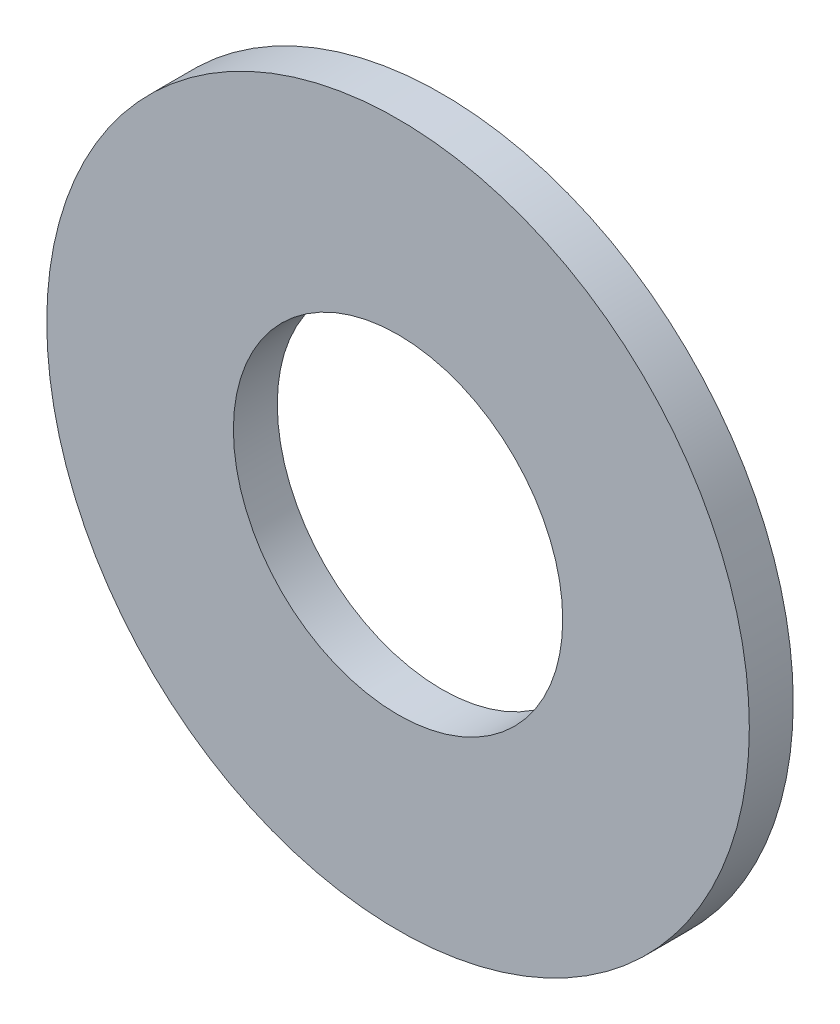
SolidWorks part; units mm, degrees
ref_plane "Front Plane" through (0, 0, 0) normal (0, 0, 1) x (1, 0, 0)
ref_plane "Top Plane" through (0, 0, 0) normal (0, 1, 0) x (1, 0, 0)
ref_plane "Right Plane" through (0, 0, 0) normal (1, 0, 0) x (0, 0, -1)
sketch "Sketch1" plane through (0, 0, 0) normal (0, 0, 1) x (1, 0, 0)
  circle A0 centre (0, 0) radius 16
  circle A1 centre (0, 0) radius 7.5
  dimension "D1" = 32
  dimension "D2" = 15
extrude "Boss-Extrude1" add sketch "Sketch1" along normal mid plane 2
